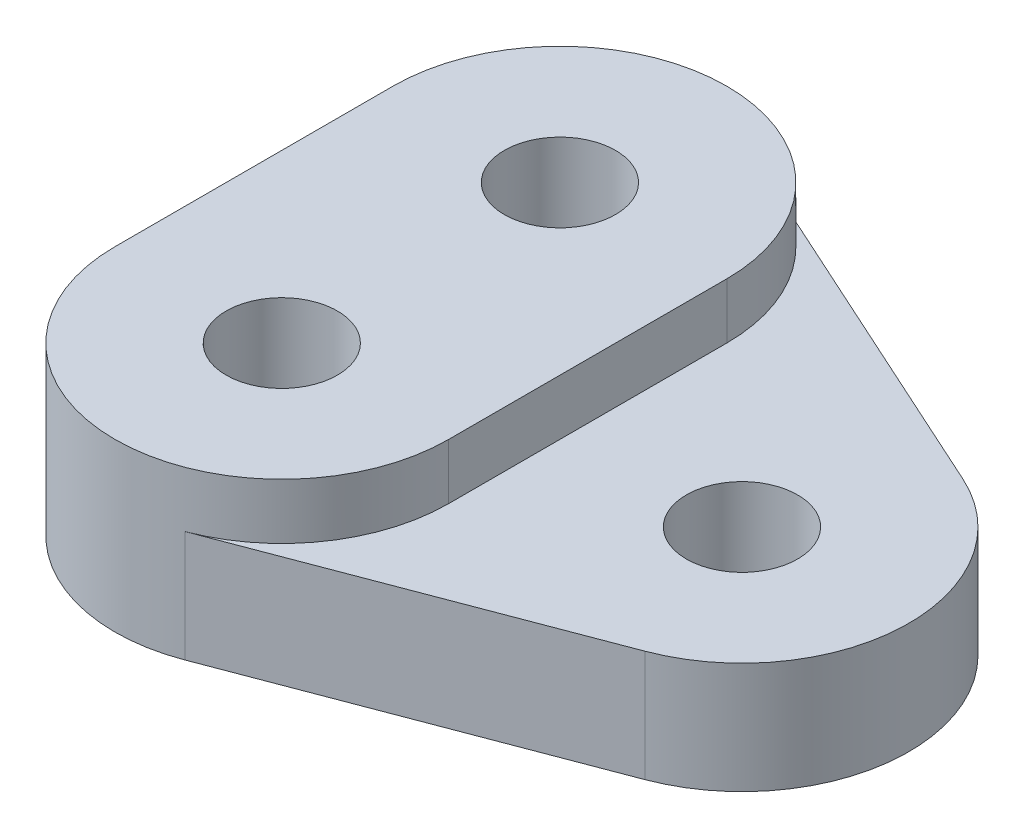
SolidWorks part; units mm, degrees
ref_plane "Front Plane" through (0, 0, 0) normal (0, 0, 1) x (1, 0, 0)
ref_plane "Top Plane" through (0, 0, 0) normal (0, 1, 0) x (1, 0, 0)
ref_plane "Right Plane" through (0, 0, 0) normal (1, 0, 0) x (0, 0, -1)
sketch "Sketch1" plane through (0, 0, 0) normal (0, 1, 0) x (1, 0, 0)
  line L0 (-6, 10) -> (-6, 0)
  line L1 (6, 10) -> (6, 0)
  line L2 (-2.097, 17.5436) -> (22.2735, 6.4678)
  line L3 (-2.4689, -7.3515) -> (24.3536, 2.8103)
  circle A0 centre (0, 0) radius 2
  circle A1 centre (0, 10) radius 2
  circle A2 centre (0, 10) radius 6
  circle A3 centre (0, 0) radius 6
  circle A4 centre (12, 4.5463) radius 2
  circle A5 centre (12, 4.5463) radius 6
  dimension "D1" = 4
  dimension "D2" = 4
  dimension "D3" = 4
  dimension "D4" = 4
  dimension "D6" = 4
  dimension "D7" = 4
  dimension "D8" = 12
  dimension "D5" = 10
extrude "Boss-Extrude1" add sketch "Sketch1" along normal blind 4 contours A3 A2 A1 | A3 A2 A0 | A3 A2 L0 | A5 L1 A3 L3 | A3 L1 A2 | A5 L2 A2 L1 | A5 A4 | A2 A3
sketch "Sketch2" plane through (0, 4, 0) normal (0, 1, 0) x (1, 0, 0)
  line L0 (6, 0) -> (6, 10)
  circle A0 centre (0, 0) radius 6
  circle A1 centre (0, 10) radius 6
  circle A2 centre (0, 0) radius 2
  circle A3 centre (0, 10) radius 2
  arc M4 (2.4825, 15.4623) -> (-6, 10) centre (0, 10) ccw
  line M5 (-6, 10) -> (-6, 0)
  arc M6 (-6, 0) -> (2.1257, -5.6108) centre (0, 0) ccw
  circle M7 centre (0, 10) radius 2
  circle M8 centre (0, 0) radius 2
extrude "Boss-Extrude2" add sketch "Sketch2" along normal blind 2 contours A1 A0 M6 M8 | A1 A0 L0 | A0 A1 | A0 A1 M4 M7 | A1 A0 M5
